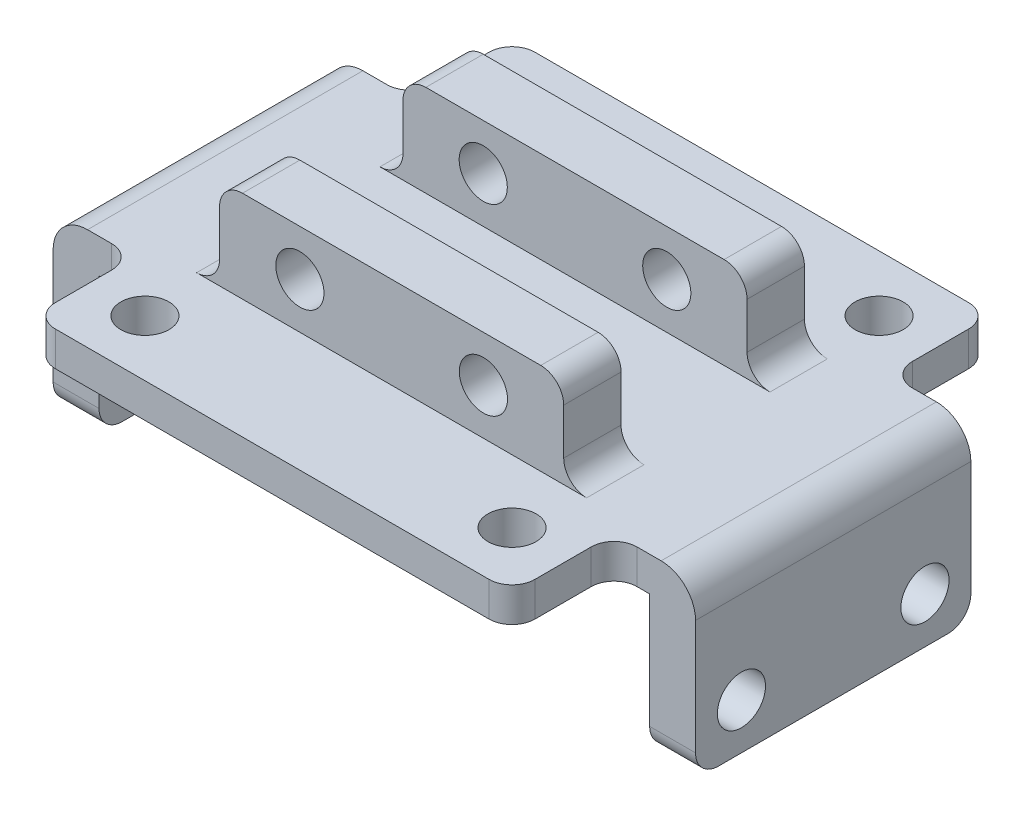
SolidWorks part; units mm, degrees
ref_plane "Front" through (0, 0, 0) normal (0, 0, 1) x (1, 0, 0)
ref_plane "Top" through (0, 0, 0) normal (0, 1, 0) x (1, 0, 0)
ref_plane "Right" through (0, 0, 0) normal (1, 0, 0) x (0, 0, -1)
sketch "Sketch1" plane through (0, 0, 0) normal (0, 1, 0) x (1, 0, 0)
  line L7 (-20.9, -20.9) -> (20.9, -20.9)
  line L8 (-20.9, -20.9) -> (-20.9, -12)
  line L9 (-20.9, 20.9) -> (20.9, 20.9)
  line L10 (20.9, -20.9) -> (20.9, -12)
  line L26 (-28, 12) -> (-20.9, 12)
  line L27 (-28, 12) -> (-28, -12)
  line L31 (-28, -12) -> (-20.9, -12)
  line L32 (-20.9, 12) -> (-20.9, 20.9)
  line L34 (28, -12) -> (20.9, -12)
  line L35 (28, 12) -> (28, -12)
  line L36 (28, 12) -> (20.9, 12)
  line L37 (20.9, 12) -> (20.9, 20.9)
  circle A0 centre (-16, 16) radius 2.1
  circle A1 centre (16, 16) radius 2.1
  circle A2 centre (16, -16) radius 2.1
  circle A3 centre (-16, -16) radius 2.1
  point P28 (-28, 0)
  point P33 (28, 0)
  dimension "D1" = 4
extrude "Boss-Extrude1" add sketch "Sketch1" along normal blind 3
sketch "Sketch2" plane through (0, 3, 0) normal (0, 1, 0) x (1, 0, 0)
  line L24 (-24, 12) -> (-24, -12)
  line L25 (-24, -12) -> (-28, -12)
  line L26 (-28, -12) -> (-28, 12)
  line L27 (-28, 12) -> (-24, 12)
  line L29 (28, 12) -> (24, 12)
  line L30 (28, -12) -> (28, 12)
  line L31 (24, -12) -> (28, -12)
  line L32 (24, 12) -> (24, -12)
extrude "Boss-Extrude2" add sketch "Sketch2" against normal blind 15
sketch "Sketch5" plane through (-28, 0, 0) normal (-1, 0, 0) x (0, 0, 1)
  circle A3 centre (-7.9996, -8) radius 2.1
  circle A4 centre (7.9996, -8) radius 2.1
  point P3 (0, -8.4781)
extrude "Cut-Extrude3" cut sketch "Sketch5" against normal blind 65
fillet "Fillet2" radius 2 12 edges at (-26, -12, -12) (-26, -12, 12) (26, -12, 12) (26, -12, -12) (20.9, 1.5, 12) (20.9, 1.5, 20.9) (-20.9, 1.5, 20.9) (-20.9, 1.5, -12) (-20.9, 1.5, -20.9) (20.9, 1.5, -20.9) (20.9, 1.5, -12) (-20.9, 1.5, 12)
fillet "Fillet3" radius 3 2 edges at (-28, 3, 0) (28, 3, 0)
sketch "Sketch6" plane through (0, 3, 0) normal (0, 1, 0) x (1, 0, 0)
  line L0 (15, 5.4923) -> (-15, 5.4923)
  line L9 (15, -5.4923) -> (-15, -5.4923)
  line L10 (15, 5.4923) -> (15, 10.4923)
  line L11 (15, 10.4923) -> (-15, 10.4923)
  line L12 (-15, 10.4923) -> (-15, 5.4923)
  line L16 (-15, -5.4923) -> (-15, -10.4923)
  line L17 (-15, -10.4923) -> (15, -10.4923)
  line L18 (15, -10.4923) -> (15, -5.4923)
  point P14 (0, 5.4923)
  point P17 (0, -5.4923)
extrude "Boss-Extrude3" add sketch "Sketch6" along normal blind 8
fillet "Fillet5" radius 2 8 edges at (15, 3, -7.9923) (15, 11, -7.9923) (-15, 11, -7.9923) (-15, 3, -7.9923) (15, 3, 7.9923) (15, 11, 7.9923) (-15, 11, 7.9923) (-15, 3, 7.9923)
sketch "Sketch9" plane through (0, 0, 10.4923) normal (0, 0, 1) x (1, 0, 0)
  circle A0 centre (-8, 7) radius 2.1
  circle A1 centre (8, 7) radius 2.1
extrude "Cut-Extrude8" cut sketch "Sketch9" against normal blind 34
